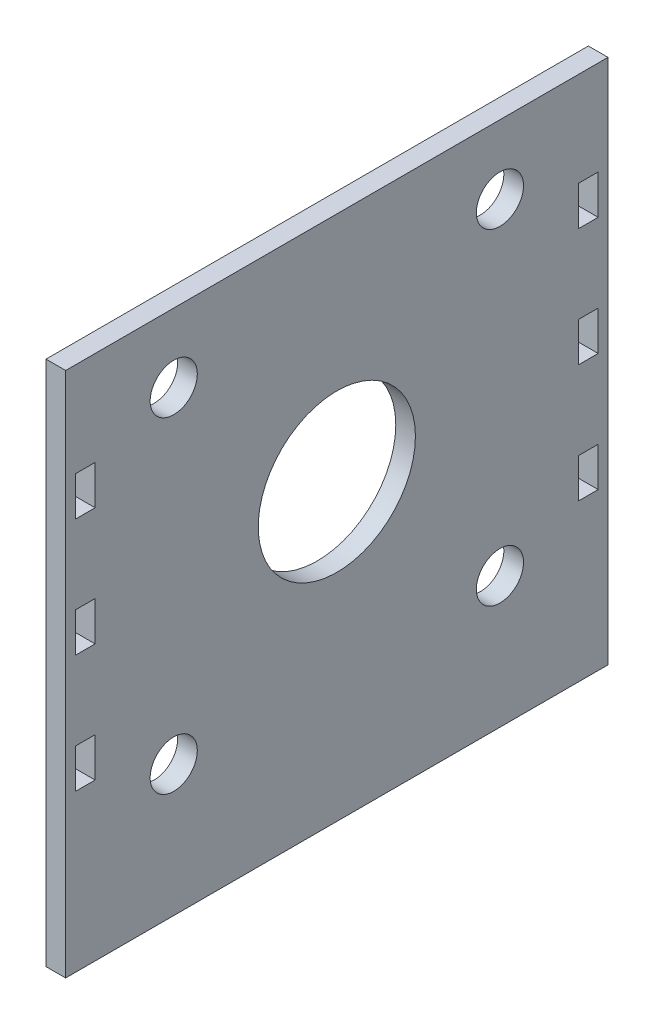
SolidWorks part; units mm, degrees
material "AISI 4130 Steel, annealed at 865C"
ref_plane "Front Plane" through (0, 0, 0) normal (0, 0, 1) x (1, 0, 0)
ref_plane "Top Plane" through (0, 0, 0) normal (0, 1, 0) x (1, 0, 0)
ref_plane "Right Plane" through (0, 0, 0) normal (1, 0, 0) x (0, 0, -1)
sketch "Sketch2" plane through (0, 0, 0) normal (1, 0, 0) x (0, 0, -1)
  line L0 (-59, 59) -> (-59, -59)
  line L1 (-54, 54) -> (54, 54) construction
  line L2 (-54, 54) -> (-54, -54) construction
  line L3 (-54, -54) -> (54, -54) construction
  line L4 (54, 54) -> (54, -54) construction
  line L5 (-54, 54) -> (54, -54) construction
  line L6 (-54, -54) -> (54, 54) construction
  line L7 (-41.5, 41.5) -> (41.5, 41.5)
  line L8 (-41.5, 41.5) -> (-41.5, -41.5)
  line L9 (-41.5, -41.5) -> (41.5, -41.5)
  line L10 (41.5, 41.5) -> (41.5, -41.5)
  line L11 (-41.5, 41.5) -> (41.5, -41.5) construction
  line L12 (-41.5, -41.5) -> (41.5, 41.5) construction
  line L13 (-59, -59) -> (59, -59)
  line L14 (59, 59) -> (59, -59)
  line L15 (-59, 59) -> (59, 59)
  point P0 (0, 0)
  point P6 (0, 0)
  dimension "D1" = 108
  dimension "D2" = 83
  dimension "D3" = 5
sketch "Sketch4" plane through (0, 0, 0) normal (1, 0, 0) x (0, 0, -1)
  line L0 (-54, -54) -> (54, 54) construction
  line L1 (-59, -59) -> (59, -59) construction
  line L2 (59, 59) -> (59, -59) construction
  line L3 (-59, 59) -> (59, 59) construction
  line L4 (-59, 59) -> (-59, -59) construction
  line L5 (-59, -59) -> (59, -59) construction
  line L6 (59, 59) -> (59, -59) construction
  line L7 (-59, 59) -> (59, 59)
  line L8 (-59, 59) -> (-59, -59) construction
  line L9 (-59, 59) -> (-69, 59)
  line L12 (-69, 59) -> (-69, -59)
  line L13 (-69, -59) -> (-59, -59) construction
  line L17 (-64, -59) -> (-64, 59) construction
  line L25 (0, 55) -> (0, -55) construction
  line L26 (-66.5, 4.9997) -> (-61.5, 4.9997)
  line L27 (-66.5, 4.9997) -> (-66.5, -4.9997)
  line L28 (-66.5, -4.9997) -> (-61.5, -4.9997)
  line L29 (-61.5, 4.9997) -> (-61.5, -4.9997)
  line L30 (-66.5, 4.9997) -> (-61.5, -4.9997) construction
  line L31 (-66.5, -4.9997) -> (-61.5, 4.9997) construction
  line L32 (-66.5, 34.9997) -> (-61.5, 34.9997)
  line L33 (-66.5, 34.9997) -> (-66.5, 25.0003)
  line L34 (-66.5, 25.0003) -> (-61.5, 25.0003)
  line L35 (-61.5, 34.9997) -> (-61.5, 25.0003)
  line L36 (-66.5, 34.9997) -> (-61.5, 25.0003) construction
  line L37 (-66.5, 25.0003) -> (-61.5, 34.9997) construction
  line L38 (-66.5, -25.0003) -> (-61.5, -25.0003)
  line L39 (-66.5, -25.0003) -> (-66.5, -34.9997)
  line L40 (-66.5, -34.9997) -> (-61.5, -34.9997)
  line L41 (-61.5, -25.0003) -> (-61.5, -34.9997)
  line L42 (-66.5, -25.0003) -> (-61.5, -34.9997) construction
  line L43 (-66.5, -34.9997) -> (-61.5, -25.0003) construction
  line L44 (66.5, 34.9997) -> (61.5, 34.9997)
  line L45 (66.5, 34.9997) -> (66.5, 25.0003)
  line L46 (66.5, 25.0003) -> (61.5, 25.0003)
  line L47 (61.5, 34.9997) -> (61.5, 25.0003)
  line L48 (66.5, -4.9997) -> (61.5, -4.9997)
  line L49 (66.5, 4.9997) -> (66.5, -4.9997)
  line L50 (66.5, 4.9997) -> (61.5, 4.9997)
  line L51 (61.5, 4.9997) -> (61.5, -4.9997)
  line L52 (66.5, -25.0003) -> (61.5, -25.0003)
  line L53 (66.5, -25.0003) -> (66.5, -34.9997)
  line L54 (61.5, -25.0003) -> (61.5, -34.9997)
  line L55 (66.5, -34.9997) -> (61.5, -34.9997)
  line L56 (69, -59) -> (59, -59) construction
  line L57 (69, 59) -> (69, -59)
  line L58 (59, 59) -> (69, 59)
  line L59 (-69, -59) -> (-69, -74.875)
  line L60 (-69, -74.875) -> (69, -74.875)
  line L61 (69, -74.875) -> (69, -59)
  circle A0 centre (41.5, 41.5) radius 6
  circle A1 centre (41.5, -41.5) radius 6
  circle A2 centre (-41.5, 41.5) radius 6
  circle A3 centre (-41.5, -41.5) radius 6
  circle A4 centre (0, 0) radius 20
  point P25 (-64, 0)
  point P30 (-64, 30)
  point P35 (-64, -30)
  dimension "D1" = 12
  dimension "D2" = 40
  dimension "D4" = 5
  dimension "D8" = 15.875
  dimension "D3" = 10
  dimension "D5" = 9.9995
  dimension "D6" = 29
  dimension "D7" = 29
extrude "Boss-Extrude2" add sketch "Sketch4" along normal blind 5 contours L58 L7 L9 L12 L13 L5 L56 L57 A4 A3 A2 A1 A0 L51 L50 L49 L48 L47 L44 L45 L46 L26 L29 L28 L27 L32 L35 L34 L33 L38 L41 L40 L39 L53 L55 L54 L52
